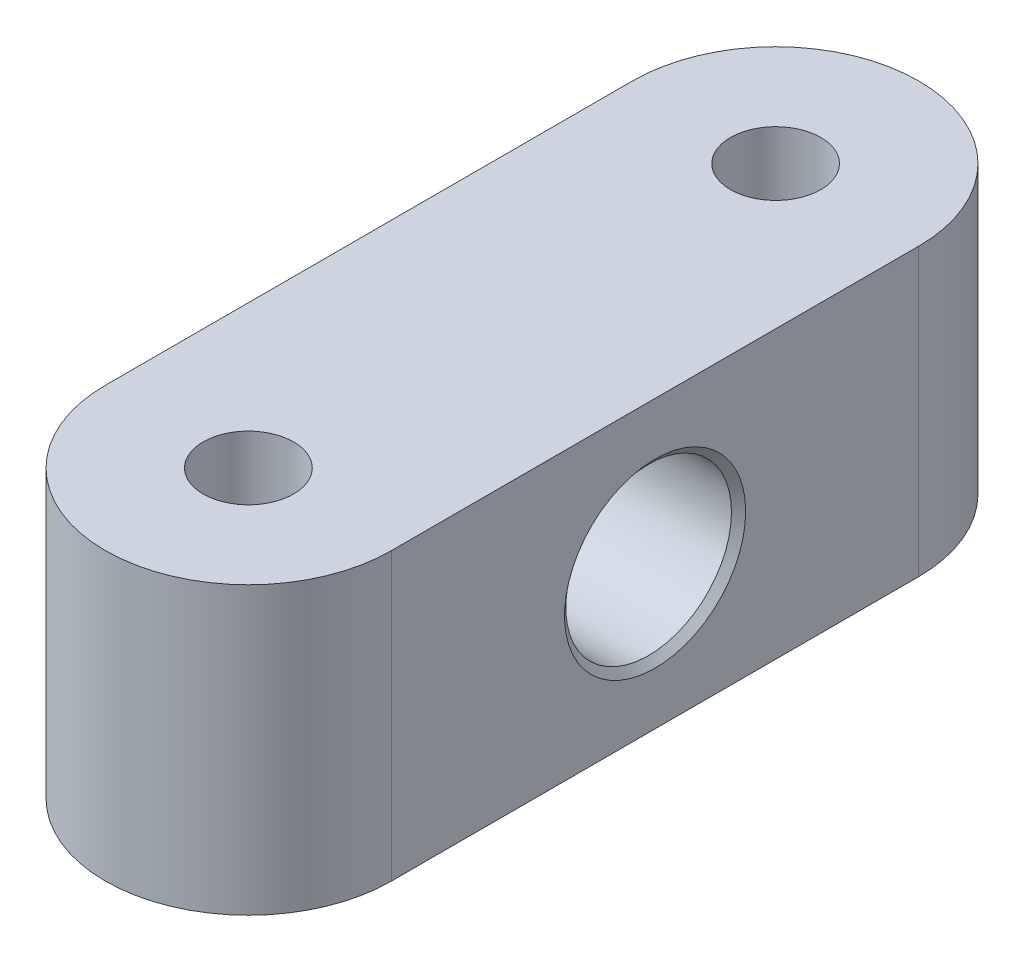
SolidWorks part; units mm, degrees
ref_plane "Front Plane" through (0, 0, 0) normal (0, 0, 1) x (1, 0, 0)
ref_plane "Top Plane" through (0, 0, 0) normal (0, 1, 0) x (1, 0, 0)
ref_plane "Right Plane" through (0, 0, 0) normal (1, 0, 0) x (0, 0, -1)
sketch "Sketch1" plane through (0, 0, 0) normal (0, 1, 0) x (1, 0, 0)
  line L0 (0, 0) -> (0, 70) construction
  line L1 (-19, 0) -> (-19, 70)
  line L2 (19, 0) -> (19, 70)
  arc A0 (-19, 0) -> (19, 0) centre (0, 0) ccw
  arc A1 (19, 70) -> (-19, 70) centre (0, 70) ccw
  circle A2 centre (0, 70) radius 6
  circle A3 centre (0, 0) radius 6
  point P3 (0, 35)
  dimension "D2" = 19
  dimension "D3" = 12
  dimension "D4" = 12
  dimension "D1" = 70
extrude "Boss-Extrude1" add sketch "Sketch1" along normal mid plane 38
hole_wizard "M24x2.0 Tapped Hole1" positions "Sketch2" profile "Sketch3" tap size "M24x2.0" standard "ANSI Metric"
sketch "Sketch2" plane through (19, 0, 0) normal (1, 0, 0) x (0, 0, -1)
  line L0 (0, 0) -> (70, 0) construction
  line L3 (35, 19) -> (35, -19) construction
  line L4 (0, 19) -> (70, 19) construction
  line L5 (0, -19) -> (70, -19) construction
  point P0 (35, 0)
sketch "Sketch3" plane through (19, 0, -35) normal (0, 1, 0) x (0, 0, -1)
  line L0 (0, 0) -> (0, 44.6095)
  line L1 (0, 44.6095) -> (11, 38)
  line L2 (11, 38) -> (11, 0.8601)
  line L3 (11, 0.8601) -> (12.025, 0)
  line L5 (12.025, 0) -> (0, 0)
  line L6 (-11, 0.8601) -> (-12.025, 0) construction
  line L10 (0, 44.6095) -> (-11, 38) construction
  line L11 (0, -6.35) -> (0, 107.95) construction
  dimension "Tap Drill Dia." = 22
  dimension "Tap Drill Depth" = 38
  dimension "Near C'Sink Dia." = 24.05
  dimension "Near C'Sink Angle" = 100
  dimension "Drill Angle" = 118
cosmetic thread "Hole Thread1" parameters "D1"=10, "D2"=24
